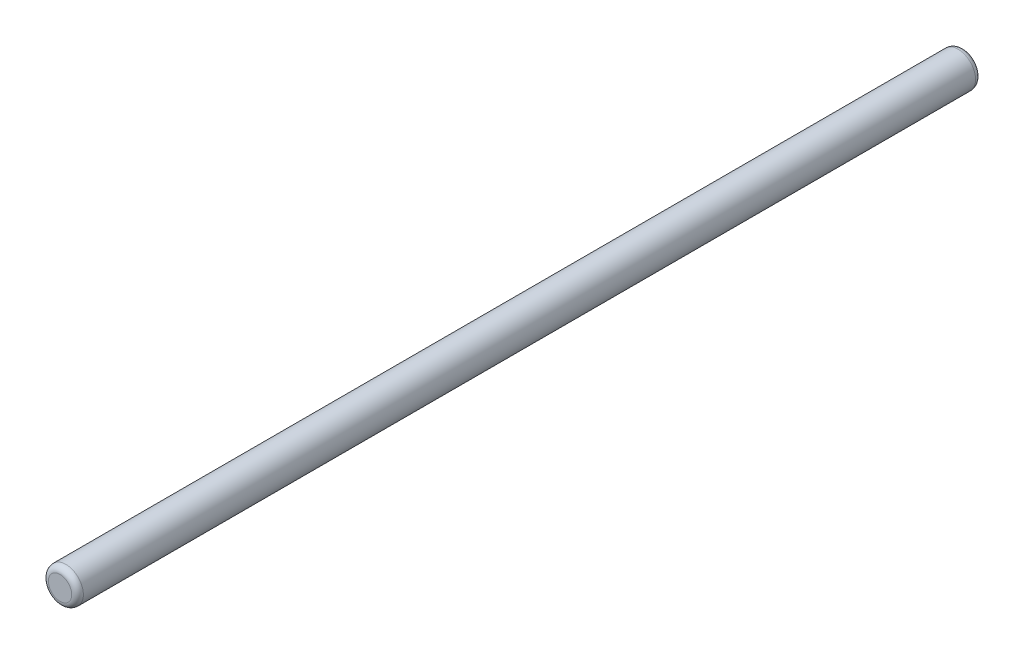
SolidWorks part; units mm, degrees
ref_plane "Ebene vorne" through (0, 0, 0) normal (0, 0, 1) x (1, 0, 0)
ref_plane "Ebene oben" through (0, 0, 0) normal (0, 1, 0) x (1, 0, 0)
ref_plane "Ebene rechts" through (0, 0, 0) normal (1, 0, 0) x (0, 0, -1)
sketch "Skizze1" plane through (0, 0, 0) normal (0, 0, 1) x (1, 0, 0)
  circle A0 centre (0, 0) radius 3
  dimension "D1" = 6
extrude "Bolzen" add sketch "Skizze1" along normal blind 155
fillet "Verrundung1" radius 1 2 edges at (3, 0, 0) (3, 0, 155)
